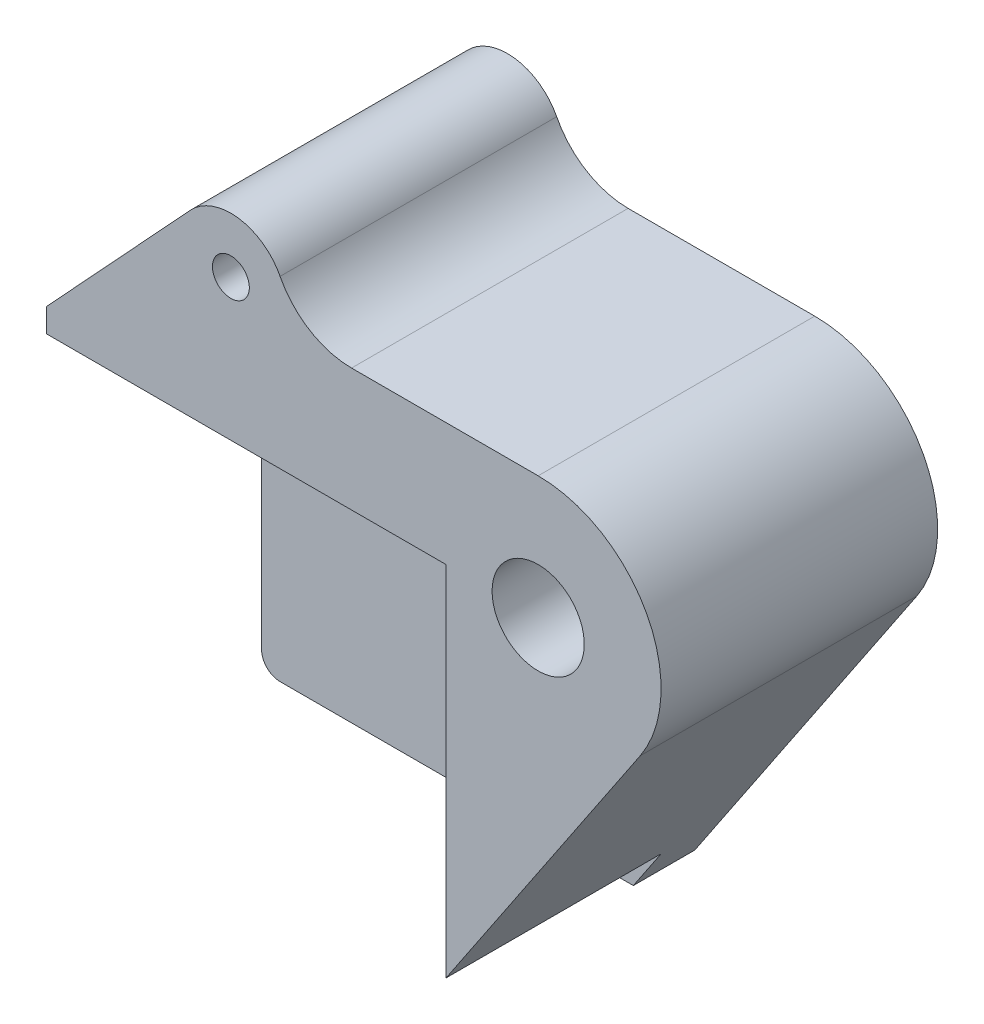
SolidWorks part; units mm, degrees
ref_plane "正面" through (0, 0, 0) normal (0, 0, 1) x (1, 0, 0)
ref_plane "平面" through (0, 0, 0) normal (0, 1, 0) x (1, 0, 0)
ref_plane "右側面" through (0, 0, 0) normal (1, 0, 0) x (0, 0, -1)
sketch "ｽｹｯﾁ1" plane through (0, 0, 0) normal (0, 0, 1) x (1, 0, 0)
  line L0 (0, 0) -> (60.4822, 0)
  line L1 (60.4822, 0) -> (96.6094, 53.8588)
  line L2 (80, 85) -> (49.6356, 85)
  line L3 (23.3974, 94.116) -> (0, 68.8573)
  line L4 (0, 68.8573) -> (0, 0)
  arc A0 (96.6094, 53.8588) -> (80, 85) centre (80, 65) ccw
  arc A1 (49.6356, 85) -> (38.0091, 92.1053) centre (49.6356, 98.0649) cw
  arc A2 (38.0091, 92.1053) -> (23.3974, 94.116) centre (30, 88) ccw
  circle A3 centre (30, 88) radius 3
  circle A4 centre (80, 65) radius 7.5
  dimension "D3" = 15
  dimension "D6" = 6
  dimension "D7" = 6
  dimension "D1" = 65
  dimension "D2" = 80
  dimension "D4" = 85
  dimension "D5" = 3
  dimension "D8" = 30
extrude "ﾎﾞｽ - 押し出し2" add sketch "ｽｹｯﾁ1" along normal blind 45
sketch "ｽｹｯﾁ3" plane through (0, 0, 45) normal (0, 0, 1) x (1, 0, 0)
  line L0 (0, 0) -> (60.4822, 0) construction
  line L1 (0, 65) -> (65, 65)
  line L2 (0, 65) -> (0, 0)
  line L3 (0, 0) -> (65, 0)
  line L4 (65, 65) -> (65, 0)
  line L5 (0, 68.8573) -> (0, 0) construction
  dimension "D1" = 65
  dimension "D2" = 65
extrude "ｶｯﾄ - 押し出し1" cut sketch "ｽｹｯﾁ3" against normal blind 35
fillet "ﾌｨﾚｯﾄ1" radius 3 1 edges at (0, 0, 5)
